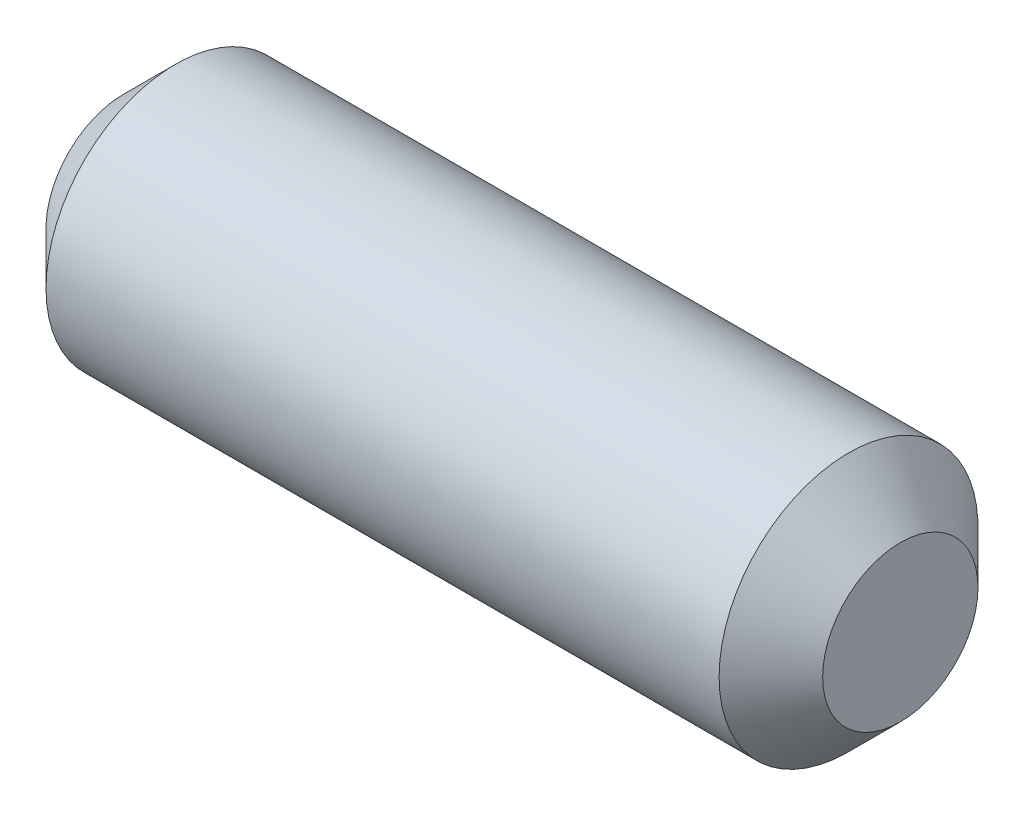
SolidWorks part; units mm, degrees
ref_plane "Front Plane" through (0, 0, 0) normal (0, 0, 1) x (1, 0, 0)
ref_plane "Top Plane" through (0, 0, 0) normal (0, 1, 0) x (1, 0, 0)
ref_plane "Right Plane" through (0, 0, 0) normal (1, 0, 0) x (0, 0, -1)
sketch "Sketch2" plane through (0, 0, 0) normal (1, 0, 0) x (0, 0, -1)
  circle A0 centre (0, 0) radius 3.175
  dimension "D1" = 6.35
extrude "Boss-Extrude1" add sketch "Sketch2" along normal blind 19.05
chamfer "Chamfer1" distance 1.27 distance2 1.27 2 edges at (0, 0, -3.175) (19.05, 0, -3.175)
equation "\"plate_diam\"= 4"
equation "\"magnet_thickness\"= 0.125"
equation "\"coupling_diam\"= 2.5"
equation "\"ball_diam\"= .375"
equation "\"dowel_diam\"= 0.25"
equation "\"plate_thickness\"= 0.47"
equation "\"magnet_diam\"=1.26"
equation "\"glue_thickness\"= 0.005"
equation "\"magnet_radial_tol\"= 0.0025"
equation "\"dowel_length\"= .75"
equation "\"dowel_center_to_center\" = 2 * ( sqr ( ( ( ( \"dowel_diam\" + \"ball_diam\" ) / 2 ) ^ 2 ) / 2 ) )"
equation "\"dowel_slot_width\"= \"dowel_center_to_center\" + \"dowel_diam\""
equation "\"dowel_slot_depth\" = \"dowel_diam\" * 0.75"
equation "\"corner_relief_diam\"= 0.25"
equation "\"central_hole_diam\"= 0.5"
equation "\"ball_center_to_slot_bottom\"= ( \"dowel_center_to_center\" / 2 ) + ( \"dowel_diam\" / 2 )"
equation "\"total_coupling_height\"= 1"
equation "\"ball_embed_depth\"= 0.15"
equation "\"ball_hole_diam\"= 2 * sqr ( ( \"ball_diam\" / 2 ) ^ 2 + - ( \"ball_diam\" / 2 - \"ball_embed_depth\" ) ^ 2 )"
equation "\"total_stack_height\"= \"plate_thickness\" - \"dowel_slot_depth\" + \"ball_center_to_slot_bottom\" + ( \"ball_diam\" / 2 ) - \"ball_embed_depth\" + \"plate_thickness\""
equation "\"D1@Sketch2\"=\"dowel_diam\""
equation "\"D1@Boss-Extrude1\"=\"dowel_length\""
